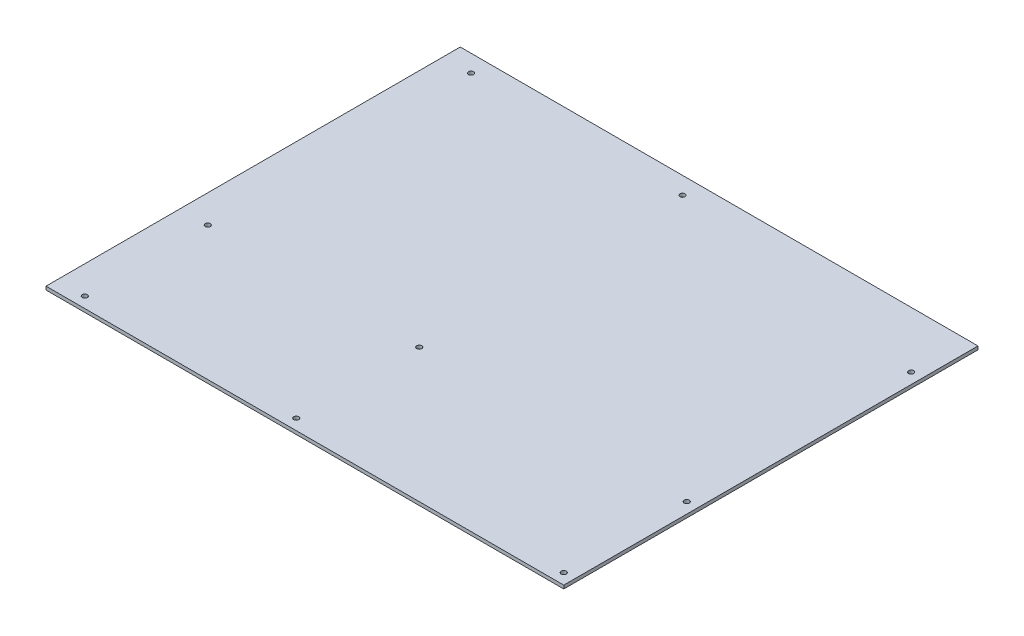
SolidWorks part; units mm, degrees
ref_plane "Спереди" through (0, 0, 0) normal (0, 0, 1) x (1, 0, 0)
ref_plane "Сверху" through (0, 0, 0) normal (0, 1, 0) x (1, 0, 0)
ref_plane "Справа" through (0, 0, 0) normal (1, 0, 0) x (0, 0, -1)
sketch "Эскиз1" plane through (0, 0, 0) normal (0, 1, 0) x (1, 0, 0)
  line L1 (0, 0) -> (304.8, 0)
  line L2 (0, 0) -> (0, 243.84)
  line L3 (0, 243.84) -> (304.8, 243.84)
  line L4 (304.8, 0) -> (304.8, 243.84)
  dimension "D1" = 243.84
  dimension "D2" = 304.8
extrude "Бобышка-Вытянуть1" add sketch "Эскиз1" along normal blind 2
sketch "Эскиз2" plane through (0, 2, 0) normal (0, 1, 0) x (1, 0, 0)
  line L0 (0, 233.68) -> (304.8, 233.68) construction
  line L1 (0, 243.84) -> (0, 0) construction
  line L2 (304.8, 0) -> (304.8, 243.84) construction
  line L3 (304.8, 243.84) -> (0, 243.84) construction
  line L4 (0, 78.74) -> (304.8, 78.74) construction
  line L5 (0, 6.35) -> (304.8, 6.35) construction
  line L6 (16.51, 0) -> (16.51, 243.84) construction
  line L7 (0, 0) -> (304.8, 0) construction
  line L8 (140.97, 0) -> (140.97, 243.84) construction
  line L9 (298.45, 0) -> (298.45, 243.84) construction
  circle A0 centre (16.51, 6.35) radius 1.5
  circle A1 centre (140.97, 6.35) radius 1.5
  circle A2 centre (298.45, 6.35) radius 1.5
  circle A3 centre (298.45, 78.74) radius 1.5
  circle A4 centre (140.97, 78.74) radius 1.5
  circle A5 centre (16.51, 78.74) radius 1.5
  circle A6 centre (16.51, 233.68) radius 1.5
  circle A7 centre (140.97, 233.68) radius 1.5
  circle A8 centre (298.45, 210.82) radius 1.5
  dimension "D7" = 3
  dimension "D1" = 10.16
  dimension "D2" = 227.33
  dimension "D3" = 154.94
  dimension "D4" = 16.51
  dimension "D5" = 124.46
  dimension "D6" = 281.94
  dimension "D8" = 22.86
extrude "Вырез-Вытянуть1" cut sketch "Эскиз2" against normal through all
